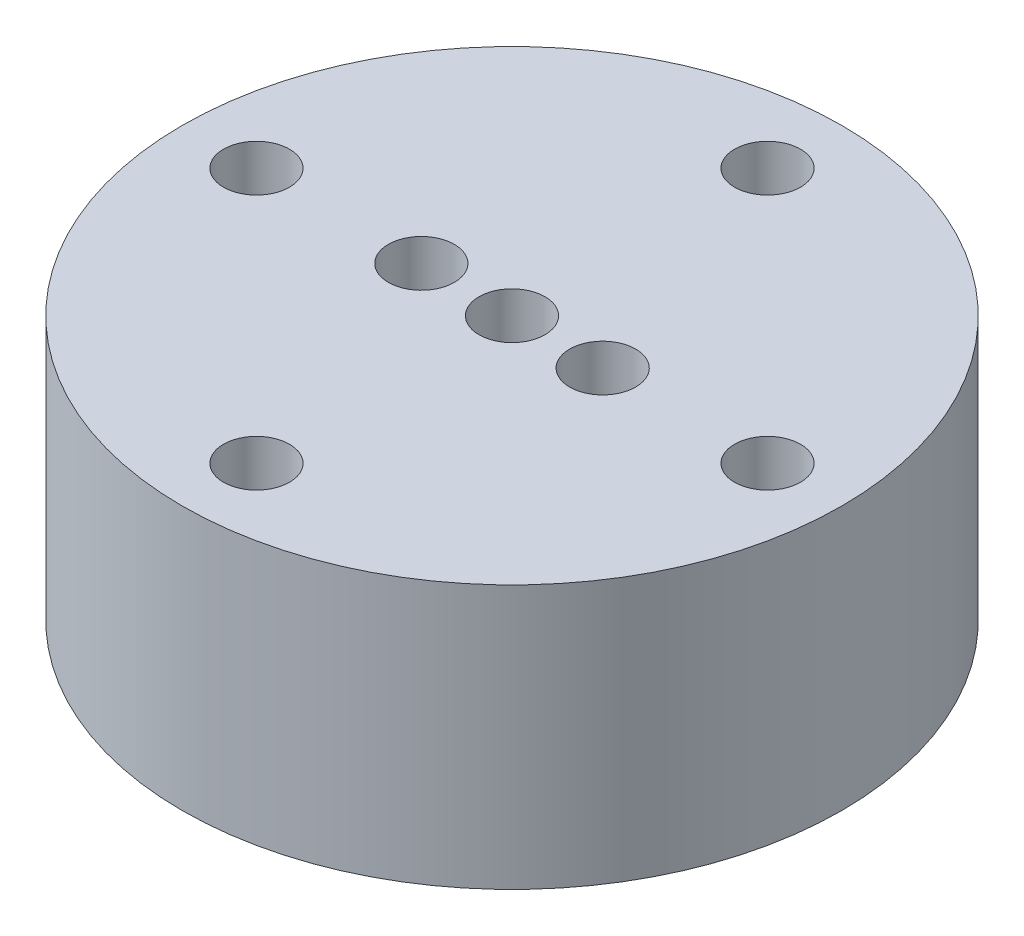
SolidWorks part; units mm, degrees
ref_plane "Front Plane" through (0, 0, 0) normal (0, 0, 1) x (1, 0, 0)
ref_plane "Top Plane" through (0, 0, 0) normal (0, 1, 0) x (1, 0, 0)
ref_plane "Right Plane" through (0, 0, 0) normal (1, 0, 0) x (0, 0, -1)
sketch "Sketch1" plane through (0, 0, 0) normal (0, 1, 0) x (1, 0, 0)
  circle A0 centre (0, 0) radius 15.5 construction
  circle A1 centre (0, 15.5) radius 2
  circle A2 centre (15.5, 0) radius 2
  circle A3 centre (0, -15.5) radius 2
  circle A4 centre (-15.5, 0) radius 2
  circle A5 centre (0, 0) radius 20
  circle A6 centre (0, 0) radius 4 construction
  point P14 (0, 0)
  dimension "D1" = 31
  dimension "D2" = 4
  dimension "D4" = 40
  dimension "D5" = 8
  dimension "D3" = 4
extrude "Boss-Extrude1" add sketch "Sketch1" along normal blind 16
sketch "Sketch2" plane through (0, 16, 0) normal (0, 1, 0) x (1, 0, 0)
  circle A0 centre (0, 0) radius 5.5 construction
  circle A1 centre (0, 0) radius 2
  circle A2 centre (5.5, 0) radius 2
  circle A3 centre (-5.5, 0) radius 2
  dimension "D1" = 11
  dimension "D2" = 4
  dimension "D3" = 4
  dimension "D4" = 4
extrude "Cut-Extrude1" cut sketch "Sketch2" against normal through all
